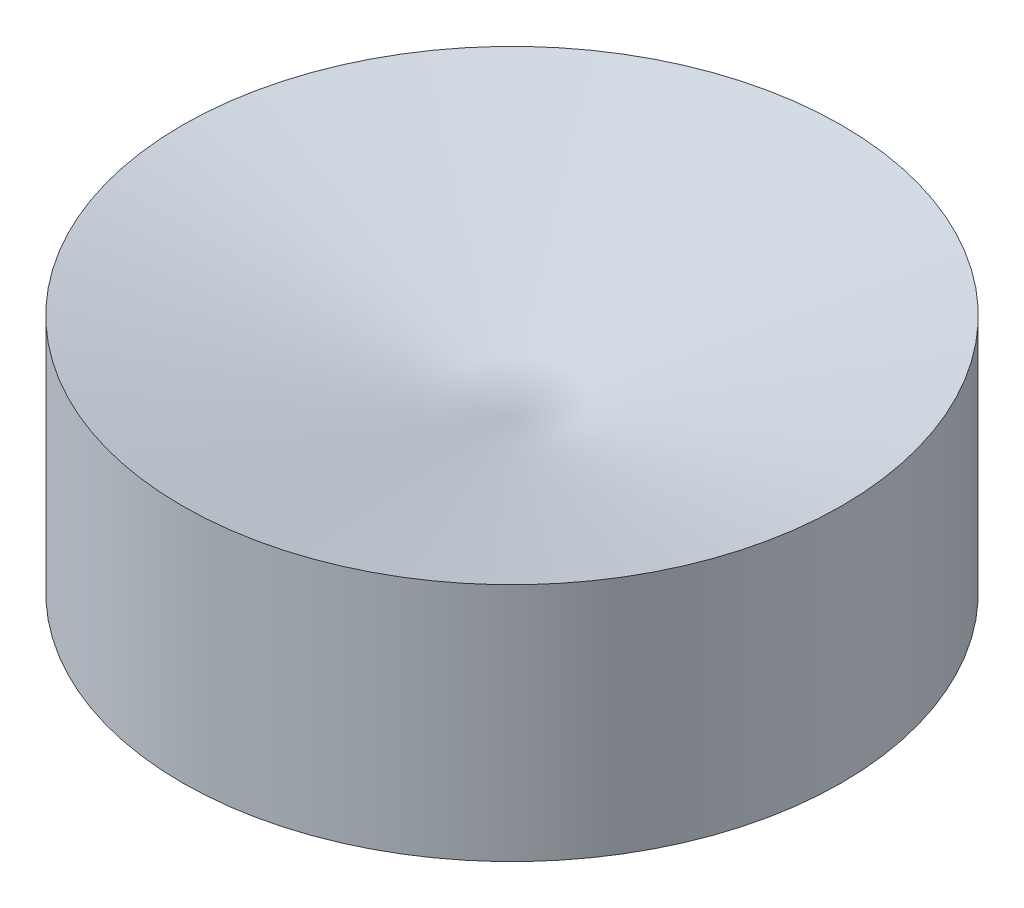
SolidWorks part; units mm, degrees
ref_plane "Front Plane" through (0, 0, 0) normal (0, 0, 1) x (1, 0, 0)
ref_plane "Top Plane" through (0, 0, 0) normal (0, 1, 0) x (1, 0, 0)
ref_plane "Right Plane" through (0, 0, 0) normal (1, 0, 0) x (0, 0, -1)
sketch "Sketch1" plane through (0, 0, 0) normal (1, 0, 0) x (0, 0, -1)
  line L0 (0, 43.0711) -> (0, -47.0674) construction
  line L1 (-55, 20) -> (-55, -20)
  line L2 (-55, -20) -> (0, -20)
  line L3 (-55, 20) -> (0, 5.2628)
  line L4 (0, -20) -> (0, 5.2628)
  point P5 (-55, 0)
  dimension "D1" = 75
  dimension "D2" = 110
  dimension "D3" = 40
revolve "Revolve1" add sketch "Sketch1" angle 360 about L0
